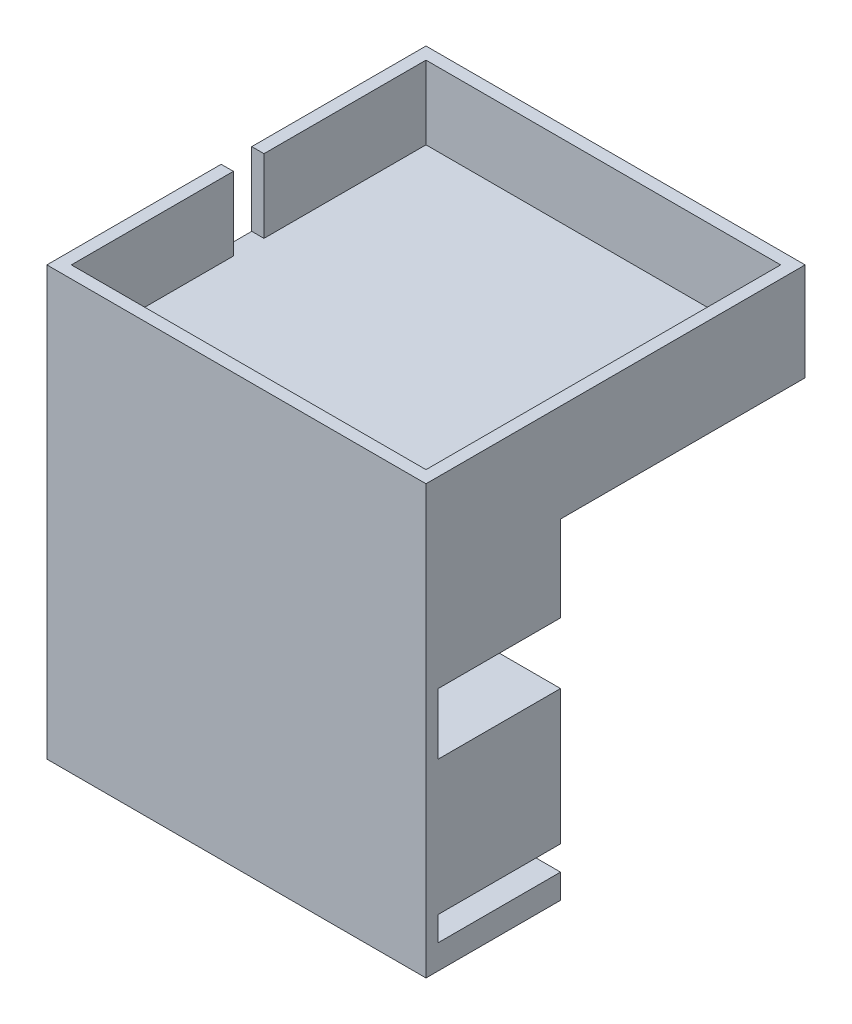
SolidWorks part; units mm, degrees
ref_plane "Alzado" through (0, 0, 0) normal (0, 0, 1) x (1, 0, 0)
ref_plane "Planta" through (0, 0, 0) normal (0, 1, 0) x (1, 0, 0)
ref_plane "Vista lateral" through (0, 0, 0) normal (1, 0, 0) x (0, 0, -1)
sketch "Croquis1" plane through (0, 0, 0) normal (0, 1, 0) x (1, 0, 0)
  line L1 (-16.5, 16.5) -> (16.5, 16.5)
  line L2 (-16.5, 16.5) -> (-16.5, -16.5)
  line L3 (-16.5, -16.5) -> (16.5, -16.5)
  line L4 (16.5, 16.5) -> (16.5, -16.5)
  line L5 (-16.5, 16.5) -> (16.5, -16.5) construction
  line L6 (-16.5, -16.5) -> (16.5, 16.5) construction
  point P0 (0, 0)
  dimension "D1" = 33
  dimension "D2" = 33
extrude "Saliente-Extruir2" add sketch "Croquis1" along normal blind 8
shell "Vaciado1" thickness 2
sketch "Croquis5" plane through (0, 8, 0) normal (0, 1, 0) x (1, 0, 0)
  line L1 (-17.8457, 1.25) -> (-13.4235, 1.25)
  line L2 (-17.8457, 1.25) -> (-17.8457, -1.25)
  line L3 (-17.8457, -1.25) -> (-13.4235, -1.25)
  line L4 (-13.4235, 1.25) -> (-13.4235, -1.25)
  line L5 (-17.8457, 1.25) -> (-13.4235, -1.25) construction
  line L6 (-17.8457, -1.25) -> (-13.4235, 1.25) construction
  point P0 (-15.6346, 0)
  dimension "D1" = 2.5
extrude "Cortar-Extruir3" cut sketch "Croquis5" against normal blind 6
sketch "Croquis6" plane through (0, 0, 0) normal (0, -1, 0) x (1, 0, 0)
  line L1 (16.5, 16.5) -> (-16.465, 16.5)
  line L2 (16.5, 16.5) -> (16.5, 4.5)
  line L3 (16.5, 4.5) -> (-16.465, 4.5)
  line L4 (-16.465, 16.5) -> (-16.465, 4.5)
  dimension "D1" = 12
extrude "Saliente-Extruir3" add sketch "Croquis6" along normal blind 27
sketch "Croquis7" plane through (0, 0, 4.5) normal (0, 0, -1) x (-1, 0, 0)
  line L0 (-16.5, -27) -> (-16.5, 0) construction
  line L1 (-16.5, -23) -> (16.465, -23)
  line L2 (-16.5, -23) -> (-16.5, -25)
  line L3 (-16.5, -25) -> (16.465, -25)
  line L4 (16.465, -23) -> (16.465, -25)
  line L5 (16.465, -27) -> (16.465, 0) construction
  line L6 (16.465, -27) -> (-16.5, -27) construction
  line L8 (-16.5, -10) -> (16.465, -10)
  line L9 (-16.5, -10) -> (-16.5, -12)
  line L10 (-16.5, -12) -> (16.465, -12)
  line L11 (16.465, -10) -> (16.465, -12)
  dimension "D1" = 2
  dimension "D2" = 2
  dimension "D3" = 13
  dimension "D4" = 2
extrude "Cortar-Extruir4" cut sketch "Croquis7" against normal blind 10
sketch "Croquis8" plane through (0, 0, 14.5) normal (0, 0, -1) x (-1, 0, 0)
  line L1 (-16.5, -12) -> (-6.5, -12)
  line L2 (-16.5, -12) -> (-16.5, -7)
  line L3 (-16.5, -7) -> (-6.5, -7)
  line L4 (-6.5, -12) -> (-6.5, -7)
  dimension "D1" = 10
  dimension "D2" = 5
extrude "Cortar-Extruir5" cut sketch "Croquis8" along normal blind 10
sketch "Croquis9" plane through (0, 8, 0) normal (0, 1, 0) x (1, 0, 0)
  line L13 (16.5, -16.5) -> (-16.5, -16.5)
  line L14 (16.5, -16.5) -> (16.5, 16.5)
  line L15 (16.5, 16.5) -> (-16.5, 16.5)
  line L16 (-16.5, -16.5) -> (-16.5, 16.5)
  line L17 (15.5, -15.5) -> (-15.5, -15.5)
  line L18 (15.5, -15.5) -> (15.5, 15.5)
  line L19 (15.5, 15.5) -> (-15.5, 15.5)
  line L20 (-15.5, -15.5) -> (-15.5, 15.5)
  dimension "D1" = 1
  dimension "D2" = 1
  dimension "D3" = 1
  dimension "D4" = 1
extrude "Cortar-Extruir6" cut sketch "Croquis9" against normal through all
